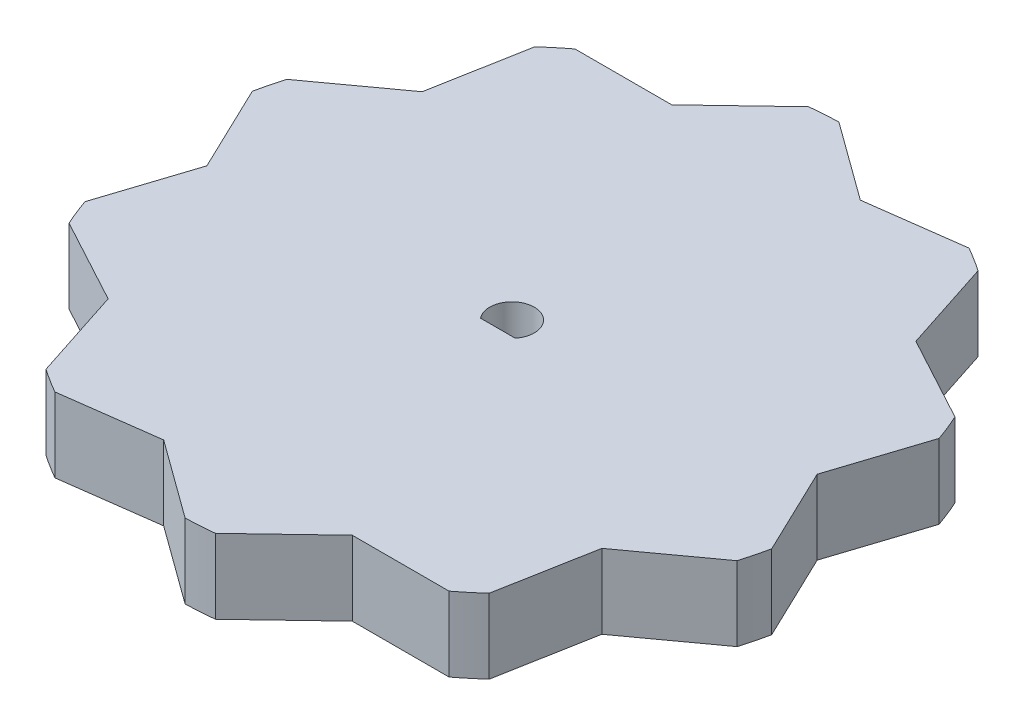
SolidWorks part; units mm, degrees
ref_plane "Front Plane" through (0, 0, 0) normal (0, 0, 1) x (1, 0, 0)
ref_plane "Top Plane" through (0, 0, 0) normal (0, 1, 0) x (1, 0, 0)
ref_plane "Right Plane" through (0, 0, 0) normal (1, 0, 0) x (0, 0, -1)
sketch "Sketch1" plane through (0, 0, 0) normal (0, 1, 0) x (1, 0, 0)
  circle A0 centre (0, 0) radius 22.5
  dimension "D1" = 45
extrude "Boss-Extrude1" add sketch "Sketch1" along normal blind 5
sketch "Sketch2" plane through (0, 5, 0) normal (0, 1, 0) x (1, 0, 0)
  line L0 (-1.1608, -0.95) -> (1.1608, -0.95)
  arc A0 (1.1608, -0.95) -> (-1.1608, -0.95) centre (0, 0) ccw
  dimension "D1" = 3
  dimension "D2" = 0.95
extrude "Cut-Extrude1" cut sketch "Sketch2" against normal blind 4
sketch "Sketch4" plane through (0, 5, 0) normal (0, 1, 0) x (1, 0, 0)
  line L0 (-2.448, 22.3664) -> (-7.1544, 17.8832)
  line L1 (-7.1544, 17.8832) -> (-13.6544, 17.8832)
  circle A0 centre (0, 0) radius 22.5 construction
  dimension "D1" = 6.5
  dimension "D2" = 6.5
extrude "Cut-Extrude6" cut sketch "Sketch4" against normal through all and the other way through all flip side to cut
sketch "Sketch5" plane through (0, 0, 0) normal (0, -1, 0) x (1, 0, 0)
  circle A0 centre (0, 0) radius 1.5
  dimension "D1" = 3
extrude "Cut-Extrude7" cut sketch "Sketch5" against normal blind 1
pattern_curve "CrvPattern3" parameters "D1"=10, "D3"=19, "D2"=1, "D4"=50
